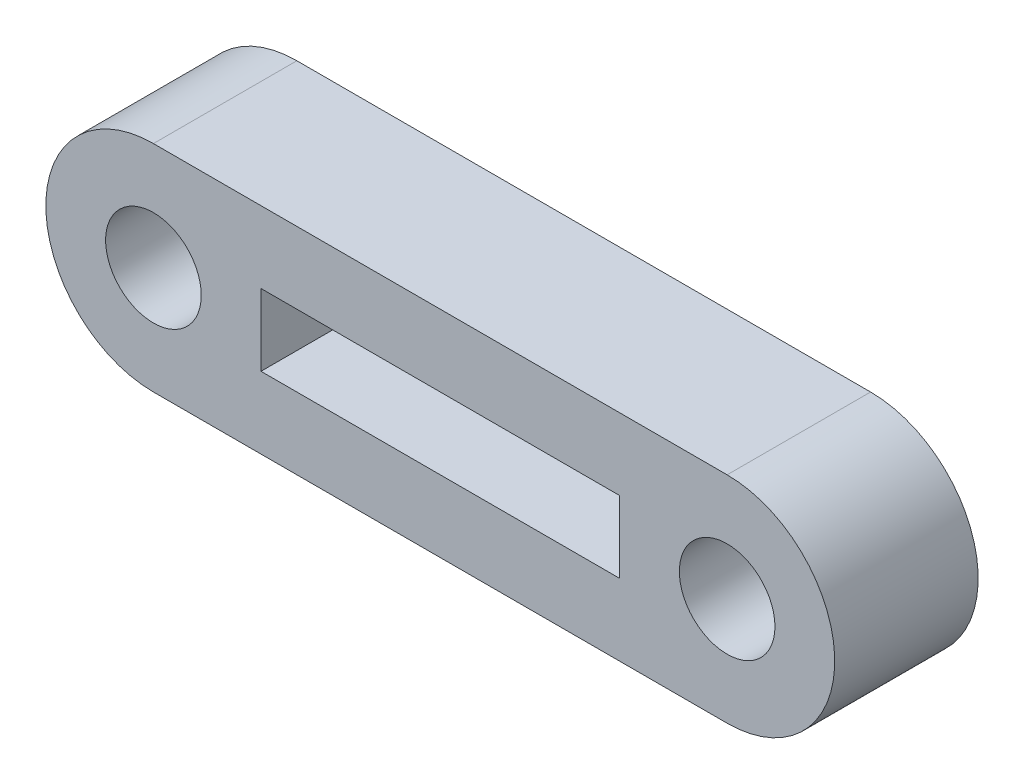
SolidWorks part; units mm, degrees
material "Pine"
ref_plane "Front Plane" through (0, 0, 0) normal (0, 0, 1) x (1, 0, 0)
ref_plane "Top Plane" through (0, 0, 0) normal (0, 1, 0) x (1, 0, 0)
ref_plane "Right Plane" through (0, 0, 0) normal (1, 0, 0) x (0, 0, -1)
sketch "Sketch1" plane through (0, 0, 0) normal (0, 0, 1) x (1, 0, 0)
  line L0 (7.5, 0) -> (-12, 0) construction
  line L1 (-7.5, 1.5) -> (7.5, 1.5)
  line L2 (-7.5, 1.5) -> (-7.5, -1.5)
  line L3 (-7.5, -1.5) -> (7.5, -1.5)
  line L4 (7.5, 1.5) -> (7.5, -1.5)
  line L5 (-7.5, 1.5) -> (7.5, -1.5) construction
  line L6 (-7.5, -1.5) -> (7.5, 1.5) construction
  line L7 (-12, 4.5) -> (12, 4.5)
  line L8 (-12, -4.5) -> (12, -4.5)
  circle A0 centre (-12, 0) radius 2
  circle A1 centre (12, 0) radius 2
  arc A4 (-12, 4.5) -> (-12, -4.5) centre (-12, 0) ccw
  arc A5 (12, -4.5) -> (12, 4.5) centre (12, 0) ccw
  point P0 (0, 0)
  dimension "D3" = 4
  dimension "D6" = 9
  dimension "D1" = 3
  dimension "D2" = 15
  dimension "D4" = 12
  dimension "D5" = 12
extrude "Boss-Extrude1" add sketch "Sketch1" along normal blind 6
